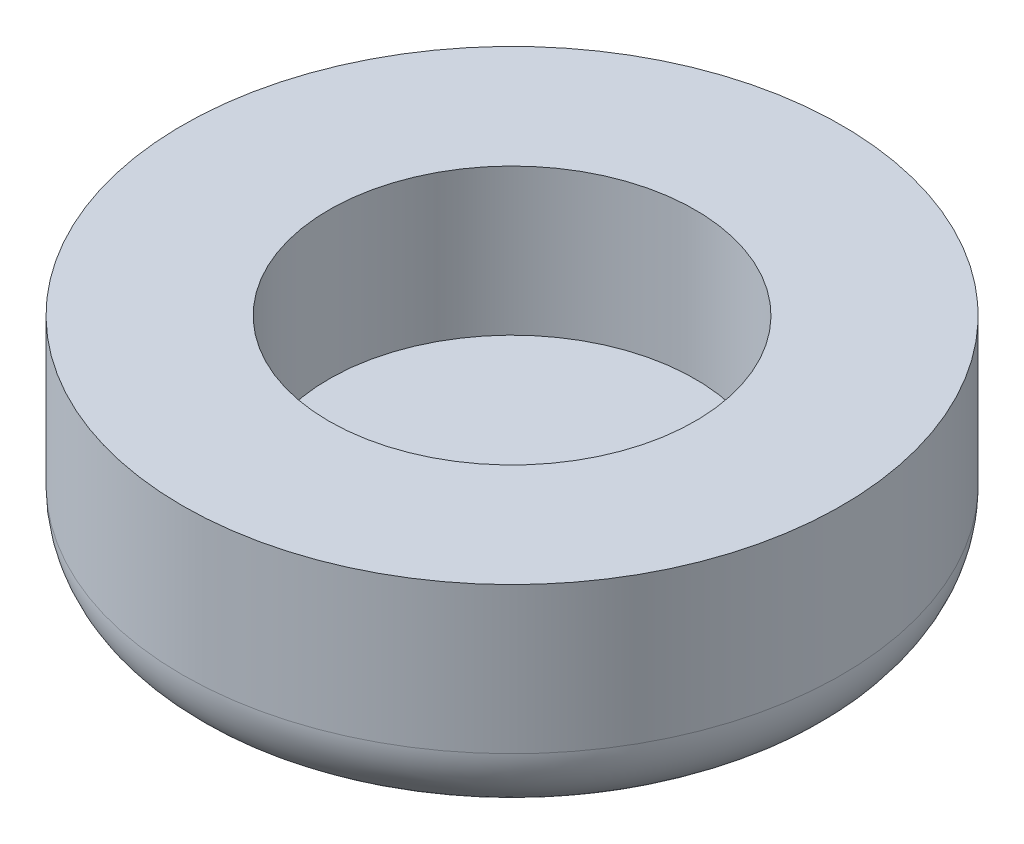
SolidWorks part; units mm, degrees
ref_plane "Front Plane" through (0, 0, 0) normal (0, 0, 1) x (1, 0, 0)
ref_plane "Top Plane" through (0, 0, 0) normal (0, 1, 0) x (1, 0, 0)
ref_plane "Right Plane" through (0, 0, 0) normal (1, 0, 0) x (0, 0, -1)
sketch "Sketch1" plane through (0, 0, 0) normal (0, 1, 0) x (1, 0, 0)
  circle A0 centre (0, 0) radius 4.5
  dimension "D1" = 9
extrude "Boss-Extrude1" add sketch "Sketch1" along normal blind 3
sketch "Sketch2" plane through (0, 3, 0) normal (0, 1, 0) x (1, 0, 0)
  circle A0 centre (0, 0) radius 2.5
  dimension "D1" = 5
extrude "Cut-Extrude1" cut sketch "Sketch2" against normal blind 2
fillet "Fillet1" radius 1 1 edges at (0, 0, 4.5)
